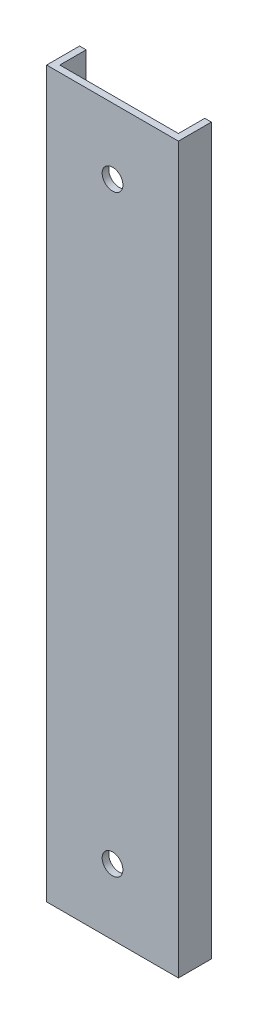
SolidWorks part; units mm, degrees
ref_plane "Front Plane" through (0, 0, 0) normal (0, 0, 1) x (1, 0, 0)
ref_plane "Top Plane" through (0, 0, 0) normal (0, 1, 0) x (1, 0, 0)
ref_plane "Right Plane" through (0, 0, 0) normal (1, 0, 0) x (0, 0, -1)
sketch "Sketch1" plane through (0, 0, 0) normal (0, 1, 0) x (1, 0, 0)
  line L0 (-22.86, 2.54) -> (-22.86, 12.7)
  line L1 (-25.4, 0) -> (25.4, 0)
  line L2 (-25.4, 0) -> (-25.4, 12.7)
  line L4 (25.4, 0) -> (25.4, 12.7)
  line L5 (-22.86, 2.54) -> (22.86, 2.54)
  line L6 (22.86, 2.54) -> (22.86, 12.7)
  line L7 (-25.4, 12.7) -> (-22.86, 12.7)
  line L8 (22.86, 12.7) -> (25.4, 12.7)
  point P0 (0, 0)
  dimension "D1" = 50.8
  dimension "D2" = 12.7
  dimension "D3" = 2.54
extrude "Boss-Extrude1" add sketch "Sketch1" along normal blind 279.4
sketch "Sketch2" plane through (0, 0, 0) normal (0, 0, 1) x (1, 0, 0)
  line L0 (-25.4, 0) -> (25.4, 0) construction
  line L1 (-25.4, 279.4) -> (25.4, 279.4) construction
  circle A0 centre (0, 25.4) radius 4
  circle A1 centre (0, 254) radius 4
  dimension "D1" = 8
  dimension "D3" = 8
  dimension "D2" = 25.4
  dimension "D4" = 25.4
extrude "Cut-Extrude1" cut sketch "Sketch2" against normal up to next
equation "\"l\" = 2"
equation "\"D1@Sketch1\"=\"l\""
equation "\"w\"= 0.5"
equation "\"D2@Sketch1\"=\"w\""
equation "\"h\" = 11"
equation "\"D1@Boss-Extrude1\"=\"h\""
equation "\"T\"=0.1"
equation "\"D3@Sketch1\"=\"T\""
equation "\"r\"=0.314961"
equation "\"D1@Sketch2\"=\"r\""
equation "\"D3@Sketch2\"=\"r\""
